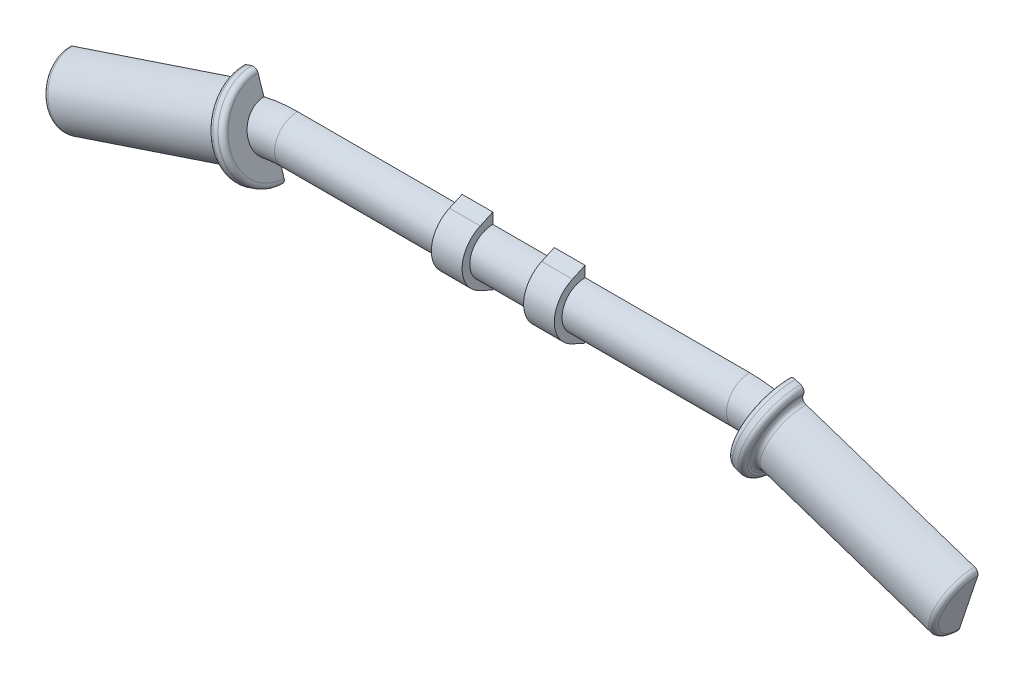
SolidWorks part; units mm, degrees
ref_plane "Front Plane" through (0, 0, 0) normal (0, 0, 1) x (1, 0, 0)
ref_plane "Top Plane" through (0, 0, 0) normal (0, 1, 0) x (1, 0, 0)
ref_plane "Right Plane" through (0, 0, 0) normal (1, 0, 0) x (0, 0, -1)
sketch "Sketch1" plane through (0, 0, 0) normal (0, 0, 1) x (1, 0, 0)
  line L0 (-6.35, 4.7625) -> (9.4615, 4.7625) construction
  line L1 (-1.6193, 3.81) -> (4.7307, 3.81)
  line L2 (-1.6193, 3.81) -> (-1.6193, -2.54)
  line L3 (-1.6193, -2.54) -> (4.7307, -2.54)
  line L4 (4.7307, 3.81) -> (4.7307, -2.54)
  dimension "D1" = 6.35
  dimension "D2" = 6.35
  dimension "D3" = 3.175
  dimension "D4" = 0.9525
extrude "Boss-Extrude1" add sketch "Sketch1" along normal blind 4.7625 contours L4 L3 L2 L1
sketch "Sketch3" plane through (4.7307, 0, 0) normal (1, 0, 0) x (0, 0, -1)
  line L0 (-4.7625, 3.81) -> (-4.7625, -2.54) construction
  line L1 (-4.7625, 3.81) -> (-8.5907, 2.0819)
  line L2 (-4.7625, -2.54) -> (-8.5907, -0.8119)
  line L3 (-4.7625, -2.54) -> (0, -2.54) construction
  line L4 (-4.7625, 3.81) -> (-4.7625, -2.54)
  line L5 (-4.7625, -2.54) -> (-4.7544, -2.5217)
  circle A0 centre (-7.9375, 0.635) radius 1.5875
  line M4 (-4.7625, 3.81) -> (-4.7625, -2.54)
  dimension "D2" = 3.175
  dimension "D1" = 3.175
  dimension "D3" = 3.175
extrude "Boss-Extrude2" add sketch "Sketch3" against normal blind 1.5875 contours A0 | A0 L2 L1 M4
sketch "Sketch4" plane through (-1.6193, 0, 0) normal (-1, 0, 0) x (0, 0, 1)
  line L0 (8.5907, -0.8119) -> (4.7625, -2.54)
  line L1 (4.7625, -2.54) -> (4.7625, 3.81)
  line L2 (4.7625, 3.81) -> (8.5907, 2.0819)
  circle A0 centre (7.9375, 0.635) radius 1.5875
  line M3 (4.7625, -2.54) -> (4.7625, 3.81)
extrude "Boss-Extrude3" add sketch "Sketch4" against normal blind 1.5875 contours A0 L2 L0 M3 | A0
sketch "Sketch5" plane through (-1.6193, 0, 0) normal (-1, 0, 0) x (0, 0, 1)
  circle A0 centre (7.9375, 0.635) radius 1.1906
  dimension "D1" = 2.3813
ref_plane "Plane1" through (0, 0, 7.9375) normal (0, 0, 1) x (1, 0, 0)
sketch "Sketch6" plane through (0, 0, 7.9375) normal (0, 0, 1) x (1, 0, 0)
  line L0 (-1.6192, 0.635) -> (4.7308, 0.635)
  line L1 (-1.6193, 1.8256) -> (-1.6193, -0.5556) construction
  line L2 (4.7307, -0.8119) -> (4.7307, 2.0819) construction
  line L3 (4.7308, 0.635) -> (13.2253, 0.635)
  line L4 (15.2333, 0.3091) -> (23.7808, -2.54)
  line L5 (-1.6192, 0.635) -> (-4.7942, 0.635)
  line L6 (-4.7942, 0.635) -> (-11.1442, -2.54)
  arc A0 (13.2253, 0.635) -> (15.2333, 0.3091) centre (13.2253, -5.715) cw
  point P12 (14.2558, 0.635)
  dimension "D7" = 6.35
  dimension "D1" = 9.525
  dimension "D2" = 9.525
  dimension "D3" = 3.175
  dimension "D4" = 3.175
  dimension "D5" = 6.35
  dimension "D6" = 3.175
sweep "Sweep1" add profiles "Sketch5" path "Sketch6"
ref_plane "Plane2" through (1.5557, 0, 0) normal (-1, 0, 0) x (0, 0, 1)
mirror "Mirror1" about plane through (1.5557, 0, 0) normal (-1, 0, 0) of "Sweep1"
sketch "Sketch7" plane through (22.1647, -7.3882, 0) normal (0.9487, -0.3162, 0) x (0, 0, -1)
  circle A0 centre (-7.9375, 5.1105) radius 1.7463
  dimension "D1" = 3.4925
extrude "Boss-Extrude4" add sketch "Sketch7" along normal blind 0.7937 and the other way blind 8.89
sketch "Sketch8" plane through (13.7309, -4.577, 0) normal (-0.9487, 0.3162, 0) x (0, 0, 1)
  circle A0 centre (7.9375, 5.1105) radius 2.3813
  dimension "D1" = 4.7625
extrude "Boss-Extrude5" add sketch "Sketch8" along normal blind 0.7937
fillet "Fillet2" radius 0.254 1 edges at (25.086, -1.1344, 7.9375)
fillet "Fillet3" radius 0.254 1 edges at (14.7947, -1.3854, 7.9375)
fillet "Fillet4" radius 0.254 2 edges at (13.8409, -1.7368, 7.9375) (14.5939, -1.9878, 7.9375)
mirror "Mirror3" about plane through (1.5557, 0, 0) normal (-1, 0, 0) of "Fillet4", "Fillet3", "Fillet2", "Boss-Extrude5", "Boss-Extrude4"
sketch "Sketch9" plane through (0, 0, 7.9375) normal (0, 0, 1) x (1, 0, 0)
  line L1 (28.0359, 4.5595) -> (-24.4756, 4.5595)
  line L2 (28.0359, 4.5595) -> (28.0359, -5.1996)
  line L3 (28.0359, -5.1996) -> (-24.4756, -5.1996)
  line L4 (-24.4756, 4.5595) -> (-24.4756, -5.1996)
extrude "Cut-Extrude1" cut sketch "Sketch9" against normal through all contours L2 L3 L4 L1
